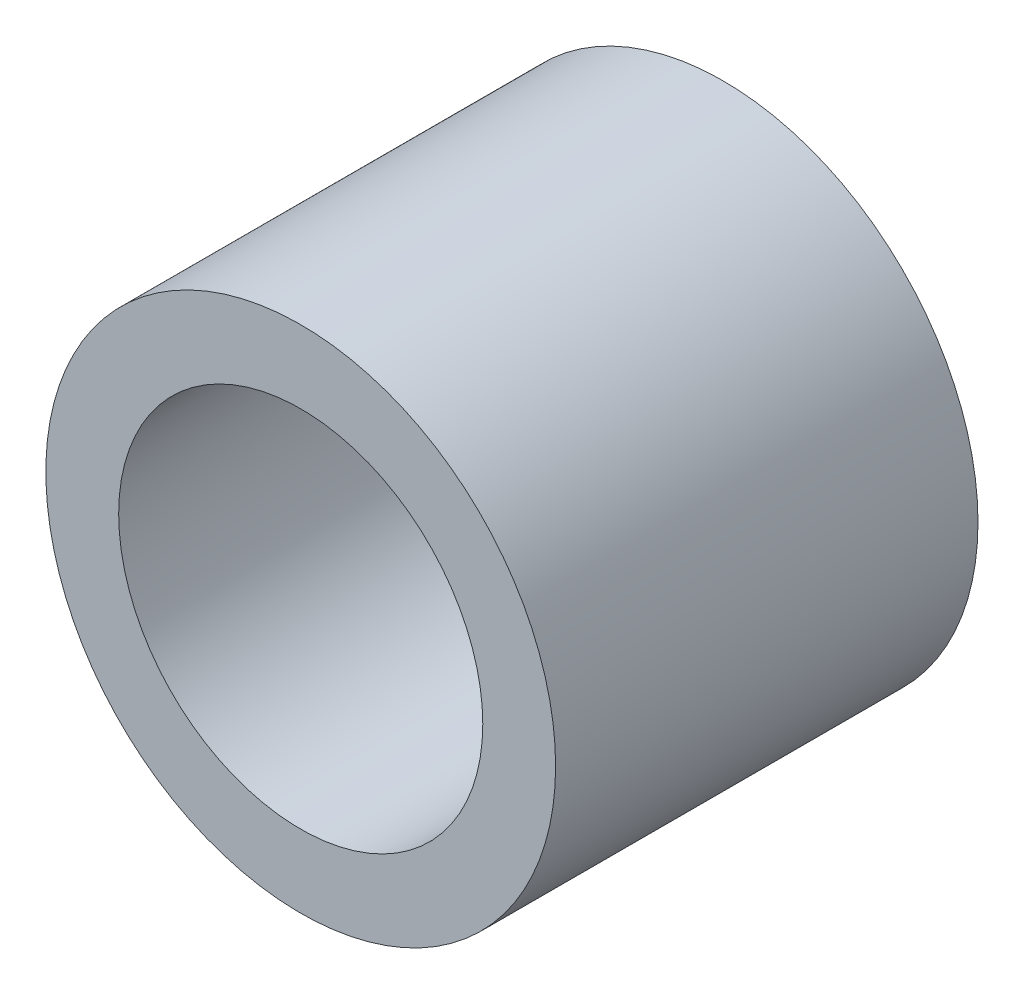
SolidWorks part; units mm, degrees
ref_plane "Front Plane" through (0, 0, 0) normal (0, 0, 1) x (1, 0, 0)
ref_plane "Top Plane" through (0, 0, 0) normal (0, 1, 0) x (1, 0, 0)
ref_plane "Right Plane" through (0, 0, 0) normal (1, 0, 0) x (0, 0, -1)
sketch "Sketch2" plane through (0, 0, 0) normal (0, 0, 1) x (1, 0, 0)
  circle A0 centre (0, 0) radius 13.335
  circle A1 centre (0, 0) radius 9.525
  dimension "D1" = 26.67
  dimension "D2" = 19.05
extrude "Boss-Extrude1" add sketch "Sketch2" along normal blind 22.098
